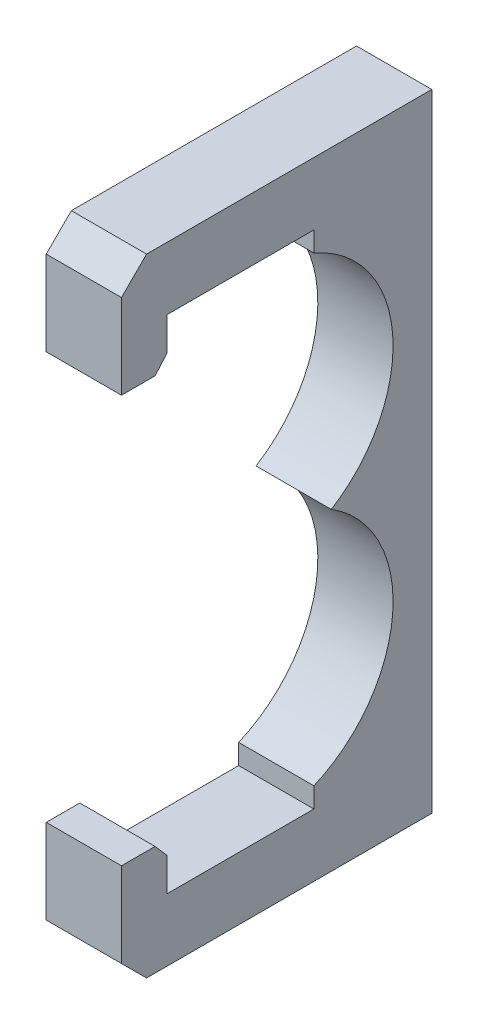
SolidWorks part; units mm, degrees
ref_plane "Front" through (0, 0, 0) normal (0, 0, 1) x (1, 0, 0)
ref_plane "Top" through (0, 0, 0) normal (0, 1, 0) x (1, 0, 0)
ref_plane "Right" through (0, 0, 0) normal (1, 0, 0) x (0, 0, -1)
sketch "Sketch1" plane through (0, 0, 0) normal (1, 0, 0) x (0, 0, -1)
  line L0 (41.2032, 15.6889) -> (43.2032, 17.6889)
  line L1 (44.8149, 12.6889) -> (44.8149, 10.0114)
  line L2 (41.2032, -23.5611) -> (41.2032, -30.3111)
  line L3 (41.2032, 8.9389) -> (43.8801, 8.9389)
  line L4 (44.8149, 12.6889) -> (56.548, 12.6889)
  line L5 (56.548, 12.6889) -> (56.548, 11.0868)
  line L6 (43.2032, 17.6889) -> (65.9487, 17.6889)
  line L7 (44.8149, 10.0114) -> (43.8801, 8.9389)
  line L8 (41.2032, 8.9389) -> (41.2032, 15.6889)
  line L9 (41.2032, -30.3111) -> (43.2032, -32.3111)
  line L11 (65.9487, 17.6889) -> (65.9487, -32.3111)
  line L12 (41.2032, -7.3111) -> (67.924, -7.3111) construction
  line L14 (44.8149, -24.6336) -> (43.8801, -23.5611)
  line L21 (43.2032, -32.3111) -> (65.9487, -32.3111)
  line L22 (56.548, -27.3111) -> (56.548, -25.709)
  line L23 (44.8149, -27.3111) -> (56.548, -27.3111)
  line L24 (41.2032, -23.5611) -> (43.8801, -23.5611)
  line L25 (44.8149, -27.3111) -> (44.8149, -24.6336)
  arc A0 (57.9343, -7.3111) -> (56.548, 11.0868) centre (52.4732, 1.5286) ccw
  arc A4 (57.9343, -7.3111) -> (56.548, -25.709) centre (52.4732, -16.1507) cw
  point P1 (41.2032, -32.3111)
  point P4 (65.9487, -7.3111)
  point P6 (41.0649, 8.9389)
  point P8 (56.548, 10.1426)
  point P13 (41.2032, 17.6889)
  point P17 (39.8149, 17.6889)
  point P18 (61.548, 17.6889)
  point P20 (52.4732, 1.754)
  point P29 (65.9487, -7.3111)
  point P30 (61.3382, 4.4643)
  dimension "D2" = 10.3905
  dimension "D7" = 1.0725
  dimension "D3" = 11.7331
  dimension "D5" = 8.75
  dimension "D6" = 2.6769
  dimension "D8" = 1.6021
extrude "Boss-Extrude1" add sketch "Sketch1" along normal blind 6
sketch "Sketch4" plane through (0, 0, -65.9487) normal (0, 0, -1) x (-1, 0, 0)
  line L0 (-18.2826, -7.2168) -> (14.6661, -7.2168) construction
  line L1 (-3, 17.6889) -> (-3, -40.8846) construction
  line L3 (-10.3426, 15.1889) -> (8.9712, 15.1889) construction
  line L4 (-6, 17.6889) -> (0, 17.6889) construction
  circle A0 centre (-3, 15.1889) radius 1.25
  circle A1 centre (-3, -29.6225) radius 1.25
  dimension "D2" = 2.5
  dimension "D1" = 2.5
extrude "Cut-Extrude1" cut sketch "Sketch4" against normal blind 6
